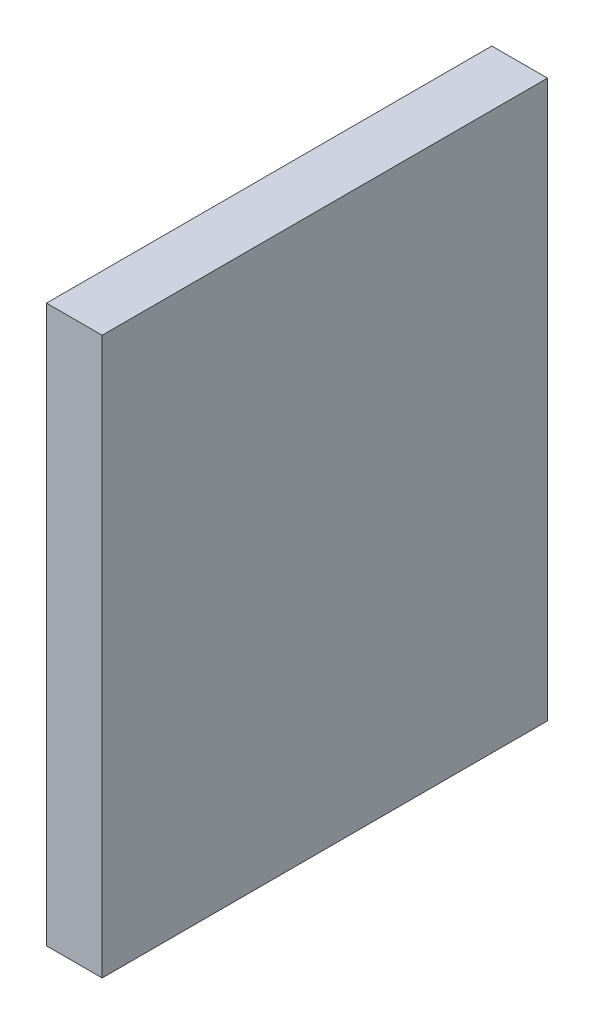
SolidWorks part; units mm, degrees
material "Teak"
ref_plane "Front Plane" through (0, 0, 0) normal (0, 0, 1) x (1, 0, 0)
ref_plane "Top Plane" through (0, 0, 0) normal (0, 1, 0) x (1, 0, 0)
ref_plane "Right Plane" through (0, 0, 0) normal (1, 0, 0) x (0, 0, -1)
sketch "Sketch1" plane through (0, 0, 0) normal (0, 1, 0) x (1, 0, 0)
  line L1 (0, 0) -> (12.7, 0)
  line L2 (0, 0) -> (0, 101.6)
  line L3 (0, 101.6) -> (12.7, 101.6)
  line L4 (12.7, 0) -> (12.7, 101.6)
  dimension "D1" = 12.7
  dimension "D2" = 101.6
extrude "Boss-Extrude1" add sketch "Sketch1" along normal blind 127
